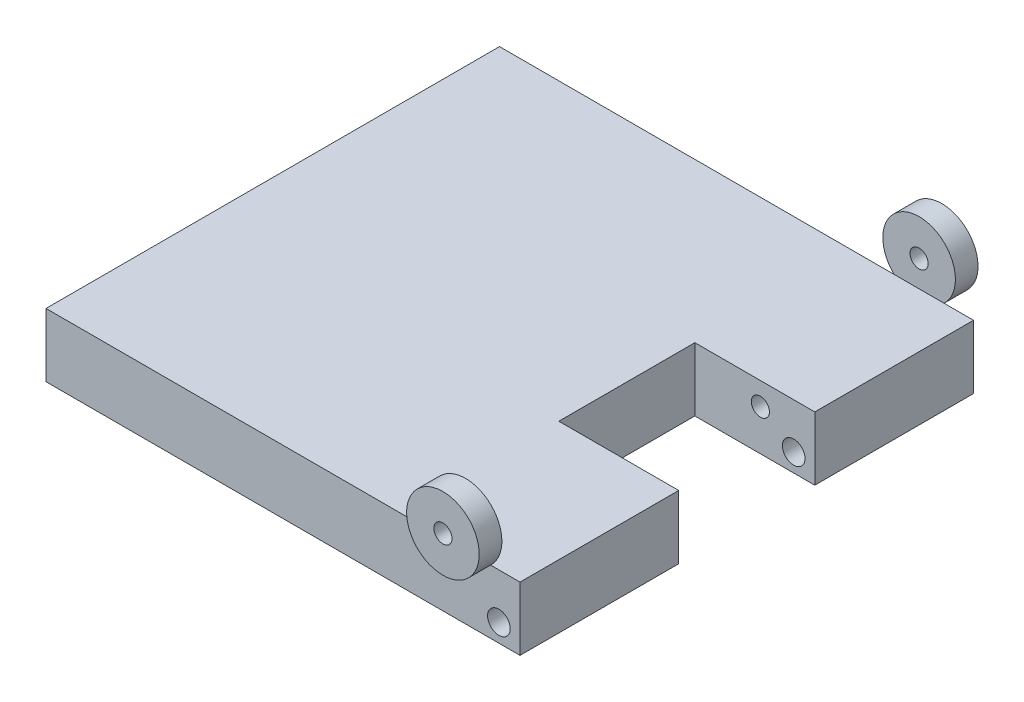
SolidWorks part; units mm, degrees
material "ABS"
ref_plane "Front Plane" through (0, 0, 0) normal (0, 0, 1) x (1, 0, 0)
ref_plane "Top Plane" through (0, 0, 0) normal (0, 1, 0) x (1, 0, 0)
ref_plane "Right Plane" through (0, 0, 0) normal (1, 0, 0) x (0, 0, -1)
sketch "Sketch1" plane through (0, 0, 0) normal (0, 0, 1) x (1, 0, 0)
  line L4 (0, 0) -> (-66.3702, 0)
  line L5 (-66.3702, 0) -> (-66.3702, 8.89)
  line L6 (-66.3702, 8.89) -> (0, 8.89)
  line L7 (0, 8.89) -> (0, 0)
  circle A6 centre (-2.9549, 2.54) radius 1.5875
  dimension "D1" = 66.3702
  dimension "D2" = 8.89
extrude "Boss-Extrude2" add sketch "Sketch1" along normal blind 63.5
sketch "Sketch2" plane through (0, 0, 0) normal (1, 0, 0) x (0, 0, -1)
  line L0 (-31.75, 8.89) -> (-22.225, 8.89)
  line L1 (-63.5, 8.89) -> (0, 8.89) construction
  line L2 (-31.75, 8.89) -> (-41.275, 8.89)
  line L4 (-41.275, 8.89) -> (-41.275, 0)
  line L5 (-63.5, 0) -> (0, 0) construction
  line L6 (-41.275, 0) -> (-22.225, 0)
  line L7 (-22.225, 0) -> (-22.225, 8.89)
extrude "Cut-Extrude1" cut sketch "Sketch2" against normal blind 16.7894
sketch "Sketch3" plane through (0, 0, 41.275) normal (0, 0, -1) x (-1, 0, 0)
  circle A0 centre (7.62, 5.715) radius 1.27
extrude "Cut-Extrude2" cut sketch "Sketch3" against normal blind 12.7
sketch "Sketch4" plane through (0, 0, 22.225) normal (0, 0, 1) x (1, 0, 0)
  circle A0 centre (-7.62, 5.715) radius 1.27
extrude "Cut-Extrude3" cut sketch "Sketch4" against normal blind 12.7
sketch "Sketch5" plane through (0, 0, 63.5) normal (0, 0, 1) x (1, 0, 0)
  circle A0 centre (-7.62, 12.573) radius 1.27
  circle A1 centre (-7.62, 12.573) radius 5.08
extrude "Boss-Extrude3" add sketch "Sketch5" along normal blind 3.175
sketch "Sketch6" plane through (0, 0, 0) normal (0, 0, -1) x (-1, 0, 0)
  line L0 (7.62, 5.715) -> (7.62, 12.573) construction
  circle A0 centre (7.62, 12.573) radius 1.27
  circle A1 centre (7.62, 12.573) radius 5.08
extrude "Boss-Extrude4" add sketch "Sketch6" along normal blind 3.175
